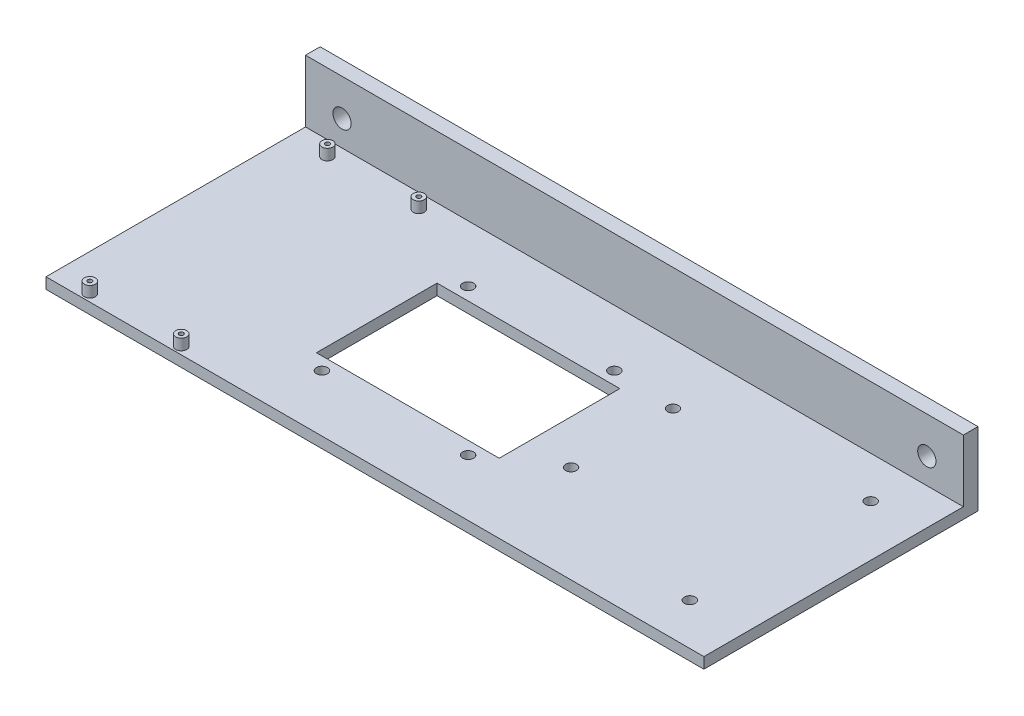
SolidWorks part; units mm, degrees
ref_plane "Front Plane" through (0, 0, 0) normal (0, 0, 1) x (1, 0, 0)
ref_plane "Top Plane" through (0, 0, 0) normal (0, 1, 0) x (1, 0, 0)
ref_plane "Right Plane" through (0, 0, 0) normal (1, 0, 0) x (0, 0, -1)
sketch "Sketch1" plane through (0, 0, 0) normal (0, 1, 0) x (1, 0, 0)
  line L1 (-90, 37.5) -> (90, 37.5)
  line L2 (-90, 37.5) -> (-90, -37.5)
  line L3 (-90, -37.5) -> (90, -37.5)
  line L4 (90, 37.5) -> (90, -37.5)
  line L5 (-90, 37.5) -> (90, -37.5) construction
  line L6 (-90, -37.5) -> (90, 37.5) construction
  point P0 (0, 0)
  dimension "D1" = 180
  dimension "D2" = 75
extrude "Boss-Extrude1" add sketch "Sketch1" along normal blind 3
sketch "Sketch2" plane through (0, 3, 0) normal (0, 1, 0) x (1, 0, 0)
  line L0 (-90, 37.5) -> (-90, -37.5) construction
  line L1 (90, 37.5) -> (-90, 37.5)
  line L2 (90, 37.5) -> (90, 33.5)
  line L3 (90, 33.5) -> (-90, 33.5)
  line L4 (-90, 37.5) -> (-90, 33.5)
  dimension "D1" = 4
extrude "Boss-Extrude2" add sketch "Sketch2" along normal offset from surface (17 mm away) 20 up to face at (0, 0, 0)
sketch "Sketch3" plane through (0, 3, 0) normal (0, 1, 0) x (1, 0, 0)
  line L0 (-1.65, 0) -> (1.65, 0) construction
  line L1 (-80, -35.5) -> (-55, -35.5) construction
  line L2 (-80, -35.5) -> (-80, 29.5) construction
  line L3 (-80, 29.5) -> (-55, 29.5) construction
  line L4 (-55, -35.5) -> (-55, 29.5) construction
  line L5 (-80, -35.5) -> (-55, 29.5) construction
  line L6 (-80, 29.5) -> (-55, -35.5) construction
  line L7 (-90, 33.5) -> (-90, -37.5) construction
  circle A0 centre (-80, 29.5) radius 1.5
  circle A1 centre (-55, 29.5) radius 1.5
  circle A2 centre (-55, -35.5) radius 1.5
  circle A3 centre (-80, -35.5) radius 1.5
  point P0 (-67.5, -3)
  dimension "D4" = 3
  dimension "D1" = 25
  dimension "D2" = 65
  dimension "D3" = 3
  dimension "D5" = 10
extrude "Boss-Extrude3" add sketch "Sketch3" along normal blind 3
sketch "Sketch4" plane through (0, 6, 0) normal (0, 1, 0) x (1, 0, 0)
  circle A0 centre (-80, 29.5) radius 0.6
  circle A1 centre (-55, 29.5) radius 0.6
  circle A2 centre (-55, -35.5) radius 0.6
  circle A3 centre (-80, -35.5) radius 0.6
  dimension "D1" = 1.2
extrude "Cut-Extrude1" cut sketch "Sketch4" against normal blind 5
sketch "Sketch5" plane through (0, 3, 0) normal (0, 1, 0) x (1, 0, 0)
  line L0 (-10, -37.5) -> (-10, 33.5) construction
  line L1 (-90, -37.5) -> (90, -37.5) construction
  line L2 (-90, 33.5) -> (90, 33.5) construction
  line L3 (0, -1.65) -> (0, 1.65) construction
  line L4 (-35, -18.5) -> (15, -18.5)
  line L5 (-35, -18.5) -> (-35, 14.5)
  line L6 (-35, 14.5) -> (15, 14.5)
  line L7 (15, -18.5) -> (15, 14.5)
  line L8 (-35, -18.5) -> (15, 14.5) construction
  line L9 (-35, 14.5) -> (15, -18.5) construction
  point P6 (-10, -2)
  point P11 (-14.3681, -2)
  dimension "D1" = 50
  dimension "D2" = 33
  dimension "D3" = 10
extrude "Cut-Extrude2" cut sketch "Sketch5" against normal blind 5
sketch "Sketch6" plane through (0, 3, 0) normal (0, 1, 0) x (1, 0, 0)
  line L0 (-35, 14.5) -> (-35, -18.5) construction
  line L1 (-30, 18) -> (10, 18) construction
  line L2 (-30, 18) -> (-30, -22) construction
  line L3 (-30, -22) -> (10, -22) construction
  line L4 (10, 18) -> (10, -22) construction
  line L5 (-30, 18) -> (10, -22) construction
  line L6 (-30, -22) -> (10, 18) construction
  line L7 (15, 14.5) -> (-35, 14.5) construction
  point P0 (-10, -2)
  point P5 (0, 0)
  point P8 (-35, -2)
  point P9 (-14.4814, -2)
  point P12 (-10, 14.5)
  point P13 (-10, -22)
  point P14 (0, 0)
  dimension "D1" = 40
hole_wizard "Ø3.0mm Dowel Hole1" positions "3DSketch1" profile "Sketch7" hole size "Ø3.0" standard "ANSI Metric" end condition through all
sketch3d "3DSketch1"
  point P0 (-30, 3, -18)
  point P3 (10, 3, -18)
  point P6 (10, 3, 22)
  point P9 (-30, 3, 22)
sketch "Sketch7" plane through (-30, 3, -18) normal (1, 0, 0) x (0, 0, 1)
  line L0 (0, 0) -> (0, 3)
  line L1 (0, 3) -> (1.5, 3)
  line L2 (1.5, 3) -> (1.5, 0)
  line L5 (1.5, 0) -> (0, 0)
  line L11 (0, -6.35) -> (0, 107.95) construction
  dimension "Thru Hole Dia." = 3
  dimension "Thru Hole Depth" = 3
sketch "Sketch8" plane through (0, 3, 0) normal (0, 1, 0) x (1, 0, 0)
  line L0 (90, -37.5) -> (90, 33.5) construction
  line L1 (21.4, 24.65) -> (90, 24.65) construction
  line L2 (21.4, 24.65) -> (21.4, -28.65) construction
  line L3 (21.4, -28.65) -> (90, -28.65) construction
  line L4 (90, 24.65) -> (90, -28.65) construction
  line L5 (21.4, 24.65) -> (90, -28.65) construction
  line L6 (21.4, -28.65) -> (90, 24.65) construction
  line L7 (27.0008, 17.05) -> (27.0008, -10.85) construction
  line L8 (76, 22.15) -> (90, 22.15) construction
  circle A1 centre (76, 22.15) radius 1.5
  circle A2 centre (74.7, -26.05) radius 1.5
  circle A3 centre (27.0008, -10.85) radius 1.5
  circle A4 centre (27.0008, 17.05) radius 1.5
  point P0 (55.7, -2)
  point P8 (27.0008, 17.05)
  point P9 (27.0008, -10.85)
  point P12 (76, 22.15)
  point P13 (74.7, -26.05)
  dimension "D9" = 3
  dimension "D1" = 68.6
  dimension "D2" = 53.3
  dimension "D3" = 27.9
  dimension "D4" = 2.5
  dimension "D5" = 14
  dimension "D6" = 1.3
  dimension "D7" = 5.1
  dimension "D8" = 15.2
extrude "Cut-Extrude3" cut sketch "Sketch8" against normal up to next
sketch "Sketch9" plane through (0, 0, -33.5) normal (0, 0, 1) x (1, 0, 0)
  line L0 (0, 20) -> (0, 3) construction
  line L1 (-90, 20) -> (90, 20) construction
  line L2 (-90, 3) -> (90, 3) construction
  line L3 (-80, 10) -> (80, 10) construction
  circle A0 centre (-80, 10) radius 2.5
  circle A1 centre (80, 10) radius 2.5
  point P9 (0, 10)
  point P11 (0, 0)
  dimension "D2" = 5
  dimension "D1" = 160
  dimension "D3" = 10
extrude "Cut-Extrude4" cut sketch "Sketch9" against normal up to next
